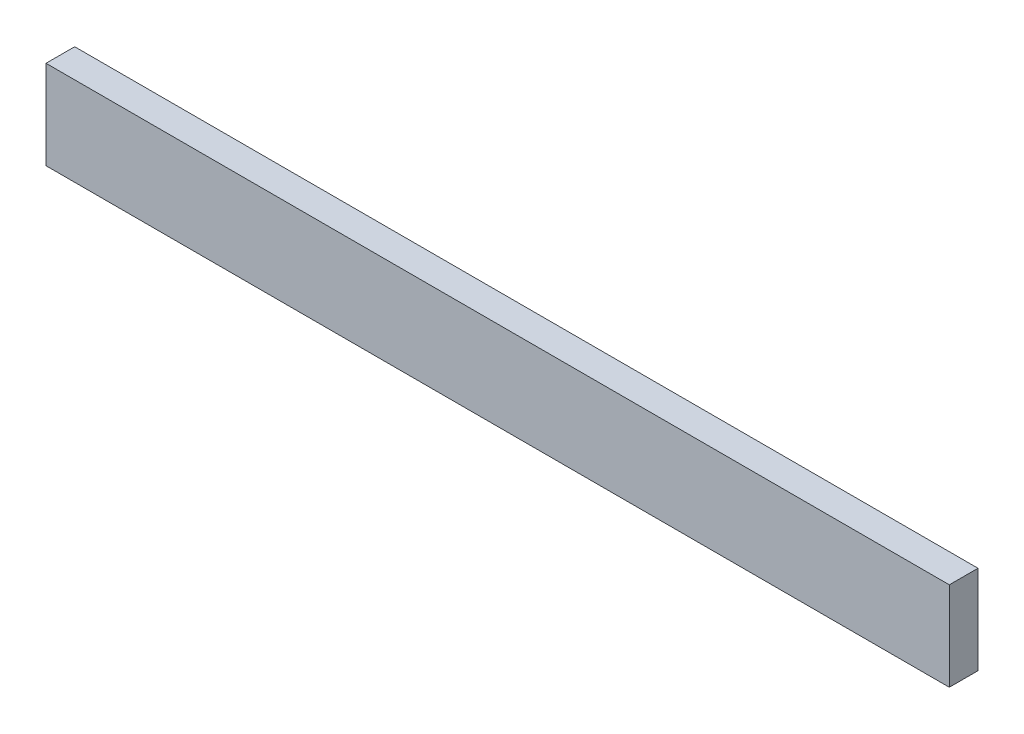
SolidWorks part; units mm, degrees
ref_plane "Front Plane" through (0, 0, 0) normal (0, 0, 1) x (1, 0, 0)
ref_plane "Top Plane" through (0, 0, 0) normal (0, 1, 0) x (1, 0, 0)
ref_plane "Right Plane" through (0, 0, 0) normal (1, 0, 0) x (0, 0, -1)
sketch "Sketch2" plane through (300, 0, 0) normal (1, 0, 0) x (0, 0, -1)
  line L1 (0, -19.05) -> (19.05, -19.05)
  line L2 (0, -19.05) -> (0, -78)
  line L3 (0, -78) -> (19.05, -78)
  line L4 (19.05, -19.05) -> (19.05, -78)
  dimension "D1" = 58.95
  dimension "D2" = 19.05
extrude "Boss-Extrude1" add sketch "Sketch2" against normal up to surface (600 mm away)
